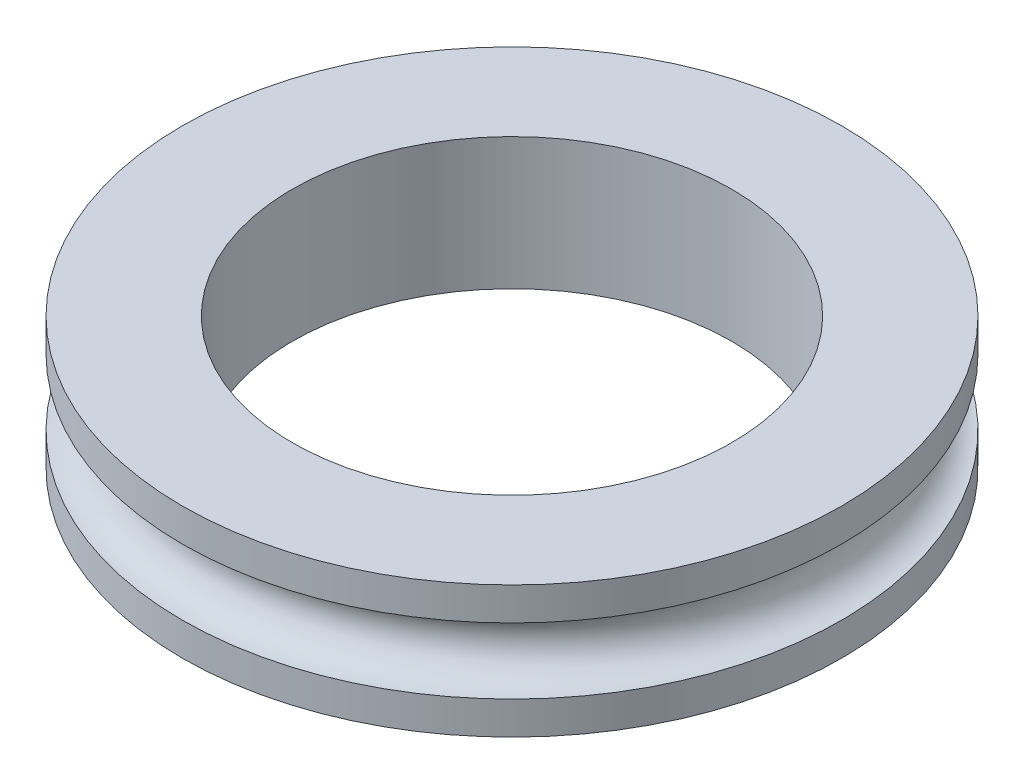
SolidWorks part; units mm, degrees
ref_plane "Alzado" through (0, 0, 0) normal (0, 0, 1) x (1, 0, 0)
ref_plane "Planta" through (0, 0, 0) normal (0, 1, 0) x (1, 0, 0)
ref_plane "Vista lateral" through (0, 0, 0) normal (1, 0, 0) x (0, 0, -1)
sketch "Croquis1" plane through (0, 0, 0) normal (0, 1, 0) x (1, 0, 0)
  circle A0 centre (0, 0) radius 7.5
  dimension "D1" = 15
extrude "Saliente-Extruir1" add sketch "Croquis1" along normal blind 3
ref_axis "Eje1" through (0, 3, 0) along (0, -1, 0)
sketch "Croquis2" plane through (0, 0, 0) normal (1, 0, 0) x (0, 0, -1)
  line L0 (7.5, 0) -> (7.5, 3) construction
  circle A0 centre (7.5, 1.5) radius 0.75
  dimension "D1" = 1.5
revolve "Cortar-Revolución1" cut sketch "Croquis2" angle 360 about axis through (0, 3, 0) along (0, -1, 0)
sketch "Croquis4" plane through (0, 0, 0) normal (0, -1, 0) x (1, 0, 0)
  circle A0 centre (0, 0) radius 5
  dimension "D1" = 10
extrude "Cortar-Extruir1" cut sketch "Croquis4" against normal through all
